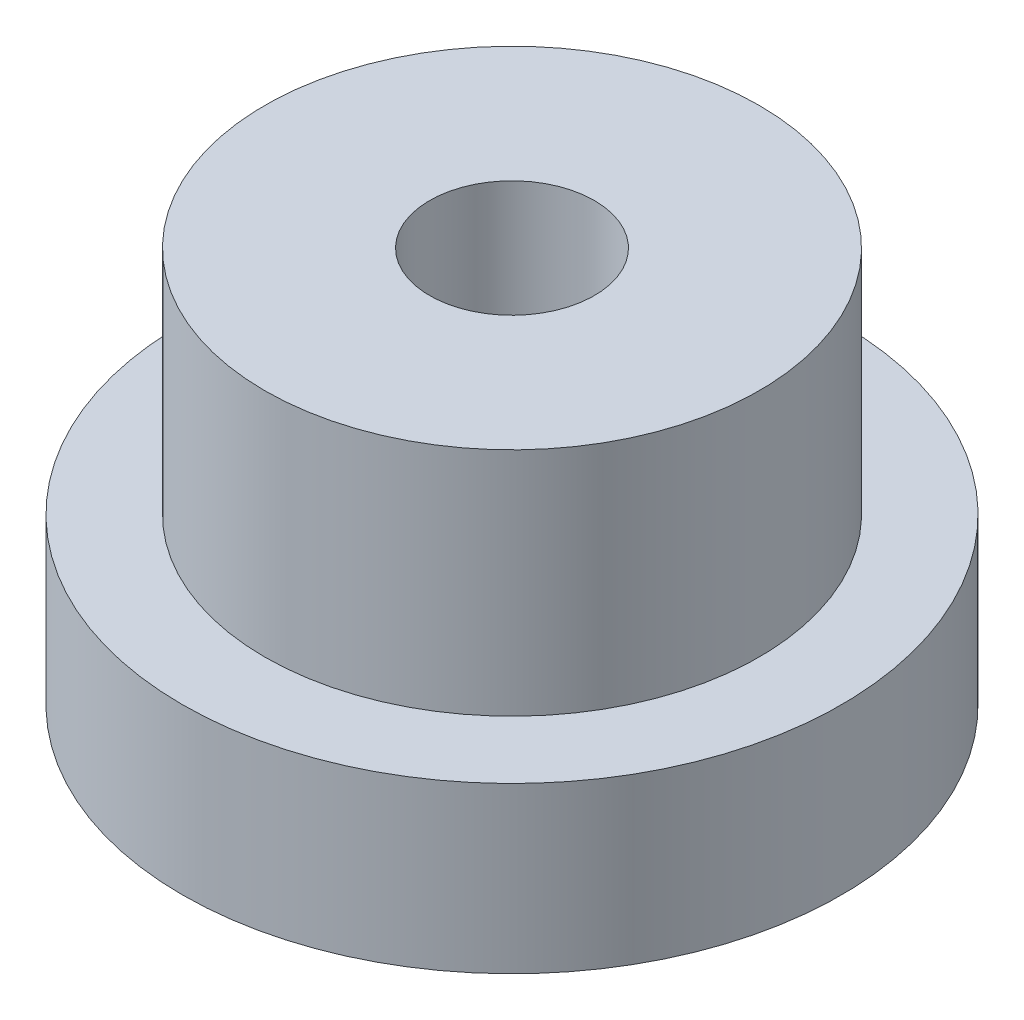
SolidWorks part; units mm, degrees
ref_plane "前视基准面" through (0, 0, 0) normal (0, 0, 1) x (1, 0, 0)
ref_plane "上视基准面" through (0, 0, 0) normal (0, 1, 0) x (1, 0, 0)
ref_plane "右视基准面" through (0, 0, 0) normal (1, 0, 0) x (0, 0, -1)
other "Configuration Table"
sketch "草图1" plane through (0, 0, 0) normal (0, 1, 0) x (1, 0, 0)
  circle A0 centre (0, 0) radius 10
  dimension "D1" = 20
extrude "凸台-拉伸1" add sketch "草图1" along normal blind 5
sketch "草图2" plane through (0, 5, 0) normal (0, 1, 0) x (1, 0, 0)
  circle A0 centre (0, 0) radius 7.5
  dimension "D1" = 15
extrude "凸台-拉伸2" add sketch "草图2" along normal blind 7
sketch "草图3" plane through (0, 0, 0) normal (0, -1, 0) x (1, 0, 0)
  circle A0 centre (0, 0) radius 2.5
  dimension "D1" = 5
extrude "切除-拉伸1" cut sketch "草图3" against normal blind 12
